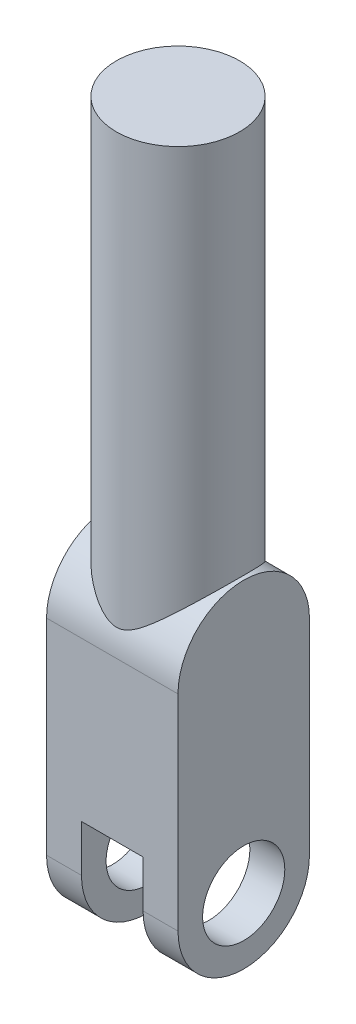
SolidWorks part; units mm, degrees
ref_plane "up基准面" through (0, 0, 0) normal (0, 0, 1) x (1, 0, 0)
ref_plane "前基准面" through (0, 0, 0) normal (0, 1, 0) x (1, 0, 0)
ref_plane "右视基准面" through (0, 0, 0) normal (1, 0, 0) x (0, 0, -1)
sketch "草图19" plane through (0, 0, 0) normal (1, 0, 0) x (0, 0, -1)
  line L0 (0, 0) -> (-15, 0)
  line L1 (-15, 0) -> (-15, -110)
  line L2 (-15, -110) -> (0, -110)
  line L3 (0, 0) -> (0, -83.9374) construction
  line L4 (0, 0) -> (0, -110)
  dimension "D1" = 110
  dimension "D2" = 15
revolve "旋转1" add sketch "草图19" angle 360 about L3
sketch "草图22" plane through (0, 0, 0) normal (1, 0, 0) x (0, 0, -1)
  line L0 (0, -110) -> (0, -160) construction
  line L1 (16, -110) -> (16, -160)
  line L2 (-16, -110) -> (-16, -160)
  arc A0 (16, -110) -> (-16, -110) centre (0, -110) ccw
  arc A1 (-16, -160) -> (16, -160) centre (0, -160) ccw
  point P3 (0, -135)
  dimension "D1" = 50
  dimension "D3" = 16
  dimension "D2" = 110
extrude "凸台-拉伸11" add sketch "草图22" along normal mid plane 32
sketch "草图23" plane through (0, 0, 0) normal (1, 0, 0) x (0, 0, -1)
  circle A0 centre (0, -160) radius 19.6289
extrude "切除-拉伸4" cut sketch "草图23" against normal mid plane 15
sketch "草图24" plane through (0, 0, 0) normal (1, 0, 0) x (0, 0, -1)
  circle A0 centre (0, -160) radius 10
extrude "切除-拉伸5" cut sketch "草图24" against normal mid plane 55
